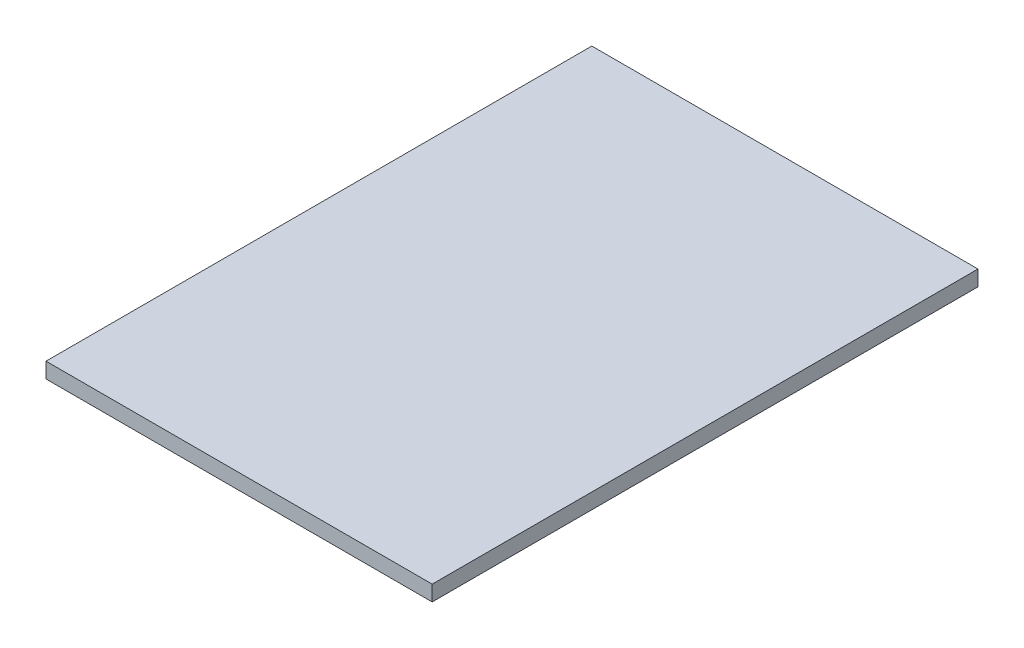
SolidWorks part; units mm, degrees
ref_plane "Front" through (0, 0, 0) normal (0, 0, 1) x (1, 0, 0)
ref_plane "Top" through (0, 0, 0) normal (0, 1, 0) x (1, 0, 0)
ref_plane "Right" through (0, 0, 0) normal (1, 0, 0) x (0, 0, -1)
sketch "Croquis1" plane through (0, 0, 0) normal (0, 1, 0) x (1, 0, 0)
  line L1 (0, 0) -> (75, 0)
  line L2 (0, 0) -> (0, 106)
  line L3 (0, 106) -> (75, 106)
  line L4 (75, 0) -> (75, 106)
  dimension "D1" = 75
  dimension "D2" = 106
extrude "Saliente-Extruir1" add sketch "Croquis1" along normal blind 3
